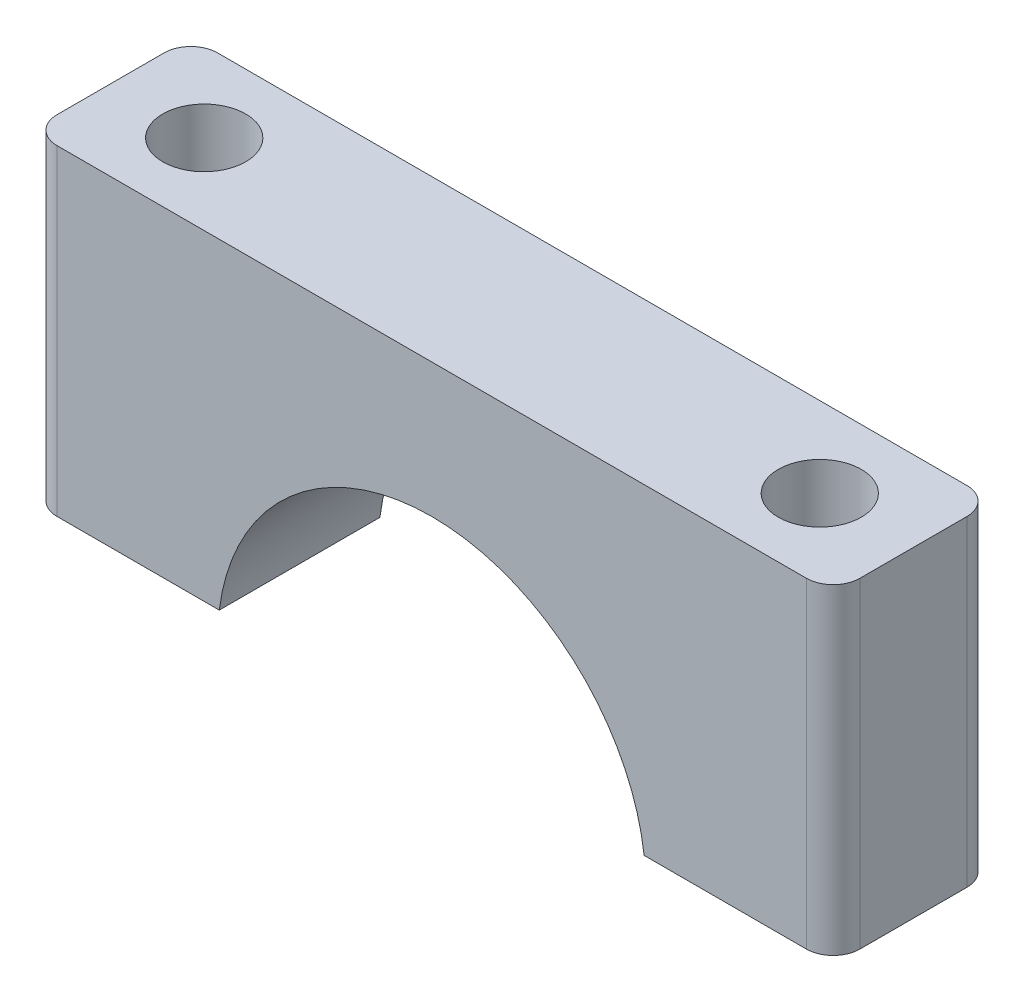
SolidWorks part; units mm, degrees
ref_plane "Front Plane" through (0, 0, 0) normal (0, 0, 1) x (1, 0, 0)
ref_plane "Top Plane" through (0, 0, 0) normal (0, 1, 0) x (1, 0, 0)
ref_plane "Right Plane" through (0, 0, 0) normal (1, 0, 0) x (0, 0, -1)
sketch "Sketch1" plane through (0, 0, 0) normal (0, 0, 1) x (1, 0, 0)
  line L1 (-15, -6) -> (15, -6)
  line L2 (-15, -6) -> (-15, 6)
  line L3 (-15, 6) -> (15, 6)
  line L4 (15, -6) -> (15, 6)
  line L5 (-15, -6) -> (15, 6) construction
  line L6 (-15, 6) -> (15, -6) construction
  point P0 (0, 0)
  dimension "D1" = 12
  dimension "D2" = 30
extrude "Boss-Extrude1" add sketch "Sketch1" along normal blind 6
sketch "Sketch2" plane through (0, 0, 6) normal (0, 0, 1) x (1, 0, 0)
  line L0 (0, -1000) -> (0, 49000) construction
  line L1 (-15, -6) -> (15, -6) construction
  circle A0 centre (0, -7) radius 8
  dimension "D1" = 16
  dimension "D2" = 1
extrude "Cut-Extrude1" cut sketch "Sketch2" against normal through all
sketch "Sketch3" plane through (0, 6, 0) normal (0, 1, 0) x (1, 0, 0)
  line L0 (-1016, -3) -> (48984, -3) construction
  line L1 (-15, -6) -> (-15, 0) construction
  circle A0 centre (-11.5, -3) radius 1.55
  circle A1 centre (11.5, -3) radius 1.55
  point P5 (-15, -3)
  dimension "D3" = 3.1
  dimension "D4" = 3.1
  dimension "D1" = 11.5
  dimension "D2" = 11.5
extrude "Cut-Extrude2" cut sketch "Sketch3" against normal through all
fillet "Fillet1" radius 1 4 edges at (15, 0, 0) (15, 0, 6) (-15, 0, 0) (-15, 0, 6)
